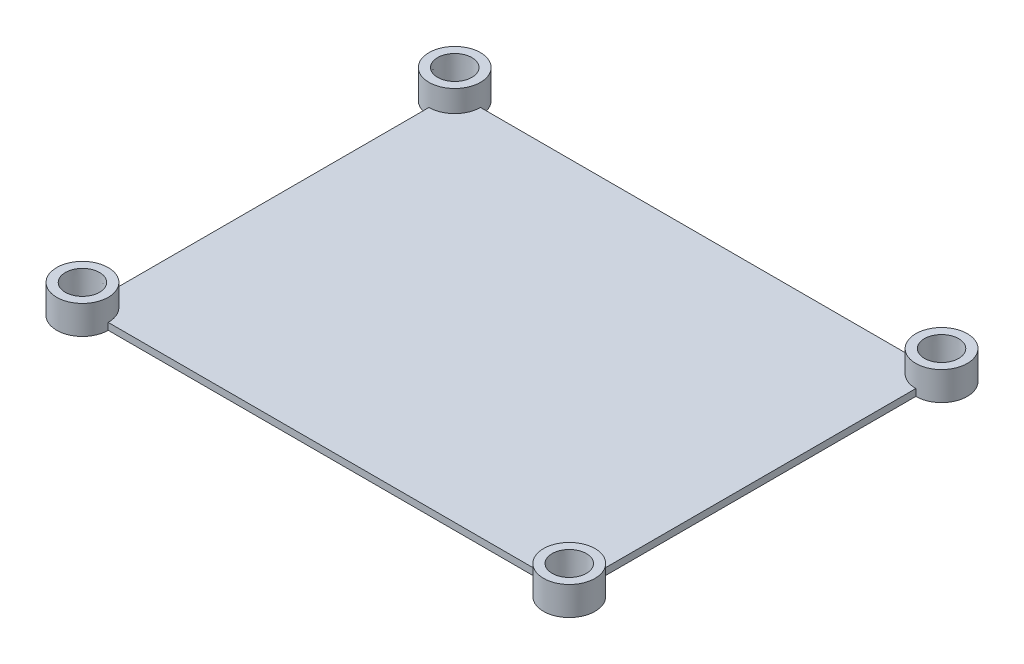
SolidWorks part; units mm, degrees
ref_plane "Front Plane" through (0, 0, 0) normal (0, 0, 1) x (1, 0, 0)
ref_plane "Top Plane" through (0, 0, 0) normal (0, 1, 0) x (1, 0, 0)
ref_plane "Right Plane" through (0, 0, 0) normal (1, 0, 0) x (0, 0, -1)
sketch "Sketch1" plane through (0, 0, 0) normal (0, 1, 0) x (1, 0, 0)
  circle A0 centre (0, 0) radius 4.5
  circle A1 centre (85, 0) radius 4.5
  circle A2 centre (85, 65) radius 4.5
  circle A3 centre (0, 65) radius 4.5
  dimension "D1" = 9
  dimension "D2" = 65
  dimension "D3" = 85
extrude "Bosses" add sketch "Sketch1" along normal blind 5
sketch "Sketch2" plane through (0, 0, 0) normal (0, 1, 0) x (1, 0, 0)
  line L1 (0, 65) -> (85, 65)
  line L2 (0, 65) -> (0, 0)
  line L3 (0, 0) -> (85, 0)
  line L4 (85, 65) -> (85, 0)
  circle A0 centre (85, 0) radius 4.5 construction
  circle A1 centre (0, 65) radius 4.5 construction
extrude "Base" add sketch "Sketch2" along normal blind 1.2
sketch "Sketch3" plane through (0, 5, 0) normal (0, 1, 0) x (1, 0, 0)
  circle A0 centre (0, 65) radius 2.995
  circle A1 centre (85, 65) radius 2.995
  circle A2 centre (85, 0) radius 2.995
  circle A3 centre (0, 0) radius 2.995
  dimension "D1" = 5.99
extrude "Insert pockets" cut sketch "Sketch3" against normal blind 4.7 draft 2
